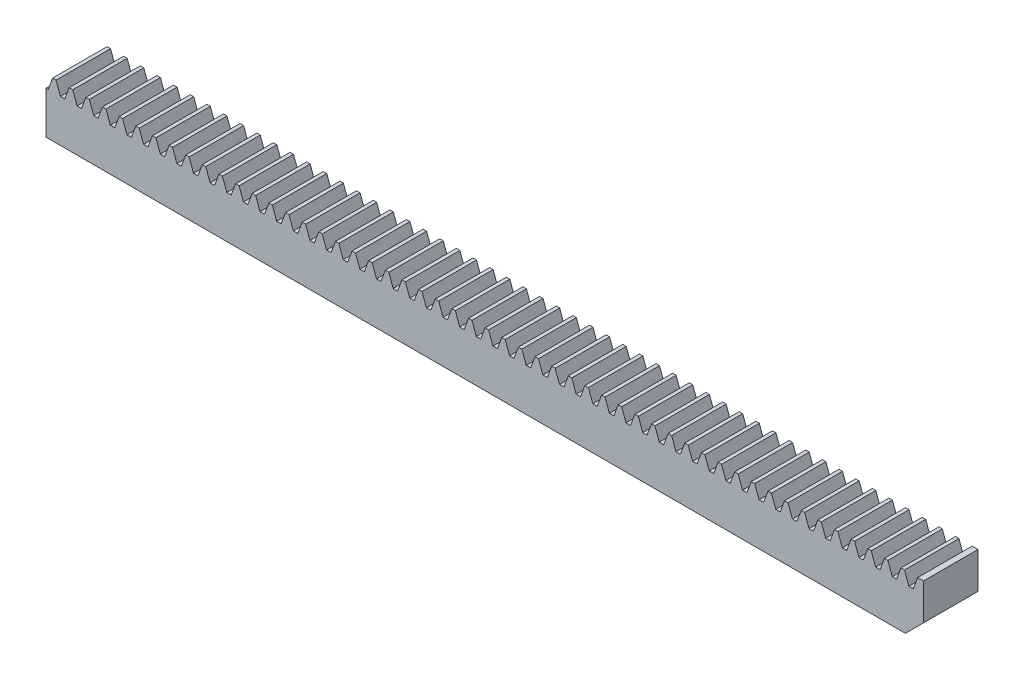
SolidWorks part; units mm, degrees
ref_plane "Front Plane" through (0, 0, 0) normal (0, 0, 1) x (1, 0, 0)
ref_plane "Top Plane" through (0, 0, 0) normal (0, 1, 0) x (1, 0, 0)
ref_plane "Right Plane" through (0, 0, 0) normal (1, 0, 0) x (0, 0, -1)
sketch "Sketch1" plane through (0, 0, 0) normal (0, 0, 1) x (1, 0, 0)
  line L1 (145, 9) -> (-145, 9)
  line L2 (145, 9) -> (145, -9)
  line L3 (145, -9) -> (-145, -9)
  line L4 (-145, 9) -> (-145, -9)
  line L5 (145, 9) -> (-145, -9) construction
  line L6 (145, -9) -> (-145, 9) construction
  point P0 (0, 0)
  dimension "D1" = 290
  dimension "D2" = 18
extrude "Boss-Extrude1" add sketch "Sketch1" along normal mid plane 18
chamfer "Chamfer1" distance 6 angle 45 1 edges at (145, -9, 0)
sketch "Sketch2" plane through (0, 0, 9) normal (0, 0, 1) x (1, 0, 0)
  line L0 (-142.8281, 9) -> (-147.1719, 9)
  line L1 (145, 9) -> (-145, 9) construction
  line L2 (-147.1719, 9) -> (-145.7379, 5.06)
  line L3 (-145.7379, 5.06) -> (-144.2621, 5.06)
  line L4 (-144.2621, 5.06) -> (-142.8281, 9)
  line L5 (-145, 9) -> (-145, -9) construction
  line L6 (-143.465, 7.25) -> (-146.535, 7.25) construction
  line L7 (-145, -9) -> (139, -9) construction
  point P4 (-145, 5.06)
  point P9 (-145, 9)
  dimension "D1" = 3.94
  dimension "D2" = 40
  dimension "D3" = 3.07
  dimension "D4" = 16.25
extrude "Cut-Extrude1" cut sketch "Sketch2" against normal through all
pattern_linear "LPattern1" count 53 spacing 5.4978 along (1, 0, 0) of "Cut-Extrude1"
hole_wizard "Ø6.0 (6) Diameter Hole1" positions "Sketch3" profile "Sketch4" hole size "Ø6.0" standard "ANSI Metric"
sketch "Sketch3" plane through (-145, 0, 0) normal (-1, 0, 0) x (0, 0, 1)
  line L0 (9, 5.06) -> (9, -9) construction
  point P0 (0, -1.97)
  point P5 (9, -1.97)
  point P6 (0, 0)
sketch "Sketch4" plane through (-145, -1.97, 0) normal (0, 1, 0) x (0, 0, 1)
  line L0 (0, 0) -> (0, 15.8026)
  line L1 (0, 15.8026) -> (3, 14)
  line L2 (3, 14) -> (3, 0)
  line L5 (3, 0) -> (0, 0)
  line L10 (0, 15.8026) -> (-3, 14) construction
  line L11 (0, -6.35) -> (0, 107.95) construction
  dimension "Hole Dia." = 6
  dimension "Hole Depth" = 14
  dimension "Drill Angle" = 118
